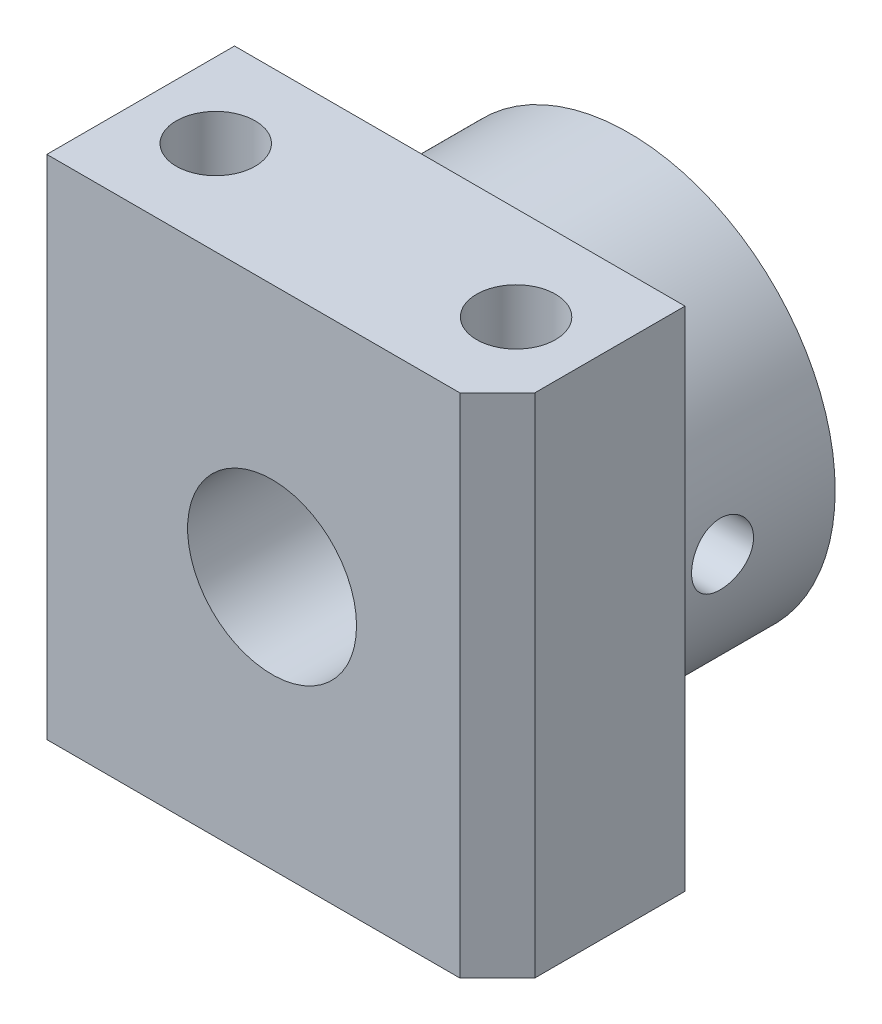
SolidWorks part; units mm, degrees
material "6061-T6 (SS)"
ref_plane "前视基准面" through (0, 0, 0) normal (0, 0, 1) x (1, 0, 0)
ref_plane "上视基准面" through (0, 0, 0) normal (0, 1, 0) x (1, 0, 0)
ref_plane "右视基准面" through (0, 0, 0) normal (1, 0, 0) x (0, 0, -1)
sketch "草图1" plane through (0, 0, 0) normal (0, 0, 1) x (1, 0, 0)
  line L1 (-12, 13.5) -> (12, 13.5)
  line L2 (-12, 13.5) -> (-12, -13.5)
  line L3 (-12, -13.5) -> (12, -13.5)
  line L4 (12, 13.5) -> (12, -13.5)
  line L5 (-12, 13.5) -> (12, -13.5) construction
  line L6 (-12, -13.5) -> (12, 13.5) construction
  point P0 (0, 0)
  dimension "D1" = 24
  dimension "D2" = 27
extrude "凸台-拉伸1" add sketch "草图1" along normal blind 10
sketch "草图2" plane through (0, 0, 0) normal (0, 0, 1) x (1, 0, 0)
  circle A0 centre (0, 0) radius 4.5
  circle A1 centre (0, 0) radius 11
  dimension "D1" = 9
  dimension "D2" = 22
extrude "凸台-拉伸2" add sketch "草图2" against normal blind 9
sketch "草图3" plane through (0, 0, 0) normal (0, 0, -1) x (-1, 0, 0)
  circle A1 centre (0, 0) radius 4.5
  circle A2 centre (0, 0) radius 4.5
  dimension "D1" = 0
extrude "切除-拉伸1" cut sketch "草图3" against normal blind 41
sketch "草图4" plane through (0, 13.5, 0) normal (0, 1, 0) x (1, 0, 0)
  line L0 (-12, -5) -> (12, -5) construction
  line L1 (-12, -10) -> (-12, 0) construction
  line L2 (12, -10) -> (12, 0) construction
  circle A0 centre (-8, -5) radius 2.1
  circle A1 centre (8, -5) radius 2.1
  dimension "D1" = 4.2
  dimension "D2" = 4.2
  dimension "D4" = 4
  dimension "D3" = 4
extrude "切除-拉伸2" cut sketch "草图4" against normal blind 37.0135
ref_plane "基准面1" through (11, 0, 0) normal (1, 0, 0) x (0, 0, -1)
sketch "草图7" plane through (11, 0, 0) normal (1, 0, 0) x (0, 0, -1)
  line L0 (0, 0) -> (3, 0) construction
  dimension "D1" = 3
chamfer "倒角1" distance 2 angle 45 1 edges at (12, 0, 10)
hole_wizard "M4 螺纹孔1" positions "草图8" profile "草图9" tap size "M4" standard "GB"
sketch "草图8" plane through (11, 0, 0) normal (1, 0, 0) x (0, 0, -1)
  point P0 (3, 0)
sketch "草图9" plane through (11, 0, -3) normal (0, 1, 0) x (0, 0, -1)
  line L0 (0, 0) -> (0, 12.4914)
  line L1 (0, 12.4914) -> (1.65, 11.5)
  line L2 (1.65, 11.5) -> (1.65, 0)
  line L5 (1.65, 0) -> (0, 0)
  line L10 (0, 12.4914) -> (-1.65, 11.5) construction
  line L11 (0, -6.35) -> (0, 107.95) construction
  dimension "螺纹孔钻头直径" = 3.3
  dimension "螺纹孔钻头深度" = 11.5
  dimension "导头角度" = 118
cosmetic thread "孔螺蚊线1" parameters "D1"=6.8134, "D2"=4
